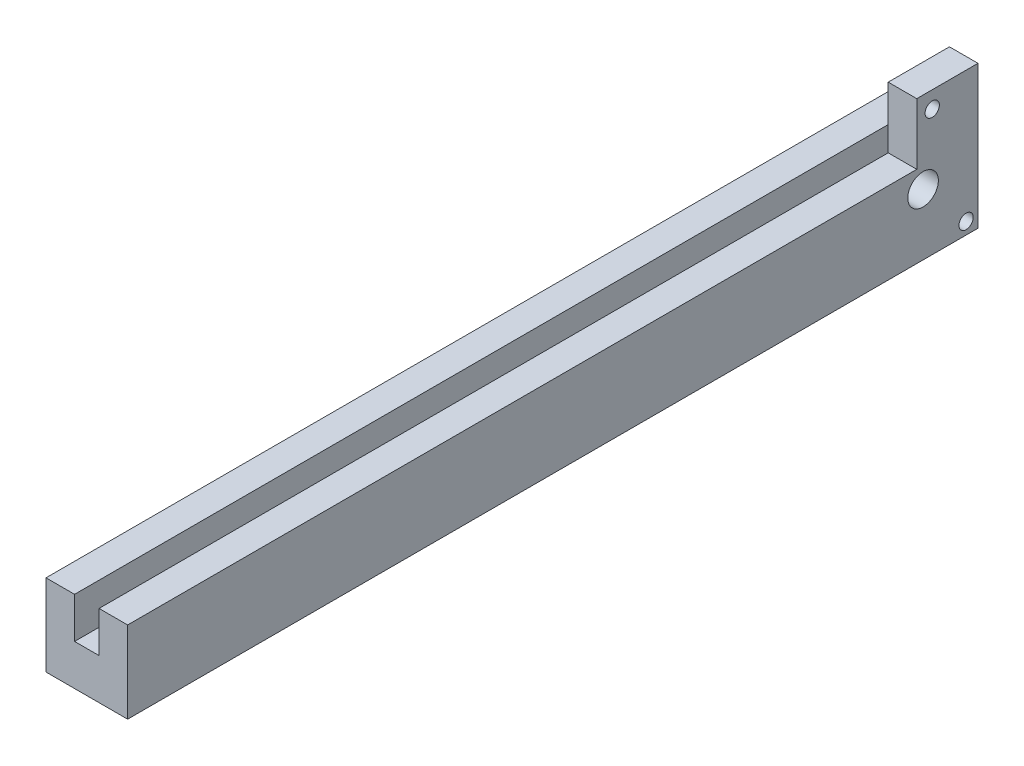
SolidWorks part; units mm, degrees
ref_plane "Front Plane" through (0, 0, 0) normal (0, 0, 1) x (1, 0, 0)
ref_plane "Top Plane" through (0, 0, 0) normal (0, 1, 0) x (1, 0, 0)
ref_plane "Right Plane" through (0, 0, 0) normal (1, 0, 0) x (0, 0, -1)
sketch "Sketch1" plane through (0, 0, 0) normal (0, 0, 1) x (1, 0, 0)
  line L1 (-12, 12) -> (12, 12)
  line L2 (-12, 12) -> (-12, -12)
  line L3 (-12, -12) -> (12, -12)
  line L4 (12, 12) -> (12, -12)
  line L5 (-12, 12) -> (12, -12) construction
  line L6 (-12, -12) -> (12, 12) construction
  point P0 (0, 0)
  dimension "D1" = 24
  dimension "D2" = 24
extrude "Boss-Extrude1" add sketch "Sketch1" along normal blind 250
sketch "Sketch2" plane through (0, 0, 250) normal (0, 0, 1) x (1, 0, 0)
  line L0 (12, 12) -> (-12, 12) construction
  line L1 (0, 0) -> (3.6, 0)
  line L2 (0, 0) -> (0, 12)
  line L3 (0, 12) -> (3.6, 12)
  line L4 (3.6, 0) -> (3.6, 12)
  dimension "D1" = 3.6
extrude "Cut-Extrude1" cut sketch "Sketch2" against normal up to surface (250 mm away) up to face at (0, 0, 0)
mirror "Mirror1" about plane through (0, 0, 0) normal (1, 0, 0) of "Cut-Extrude1"
sketch "Sketch8" plane through (0, 12, 0) normal (0, 1, 0) x (1, 0, 0)
  line L0 (12, -250) -> (12, 0) construction
  line L1 (3.6, 0) -> (12, 0)
  line L2 (3.6, 0) -> (3.6, -18)
  line L3 (3.6, -18) -> (12, -18)
  line L4 (12, 0) -> (12, -18)
  dimension "D1" = 18
extrude "Boss-Extrude2" add sketch "Sketch8" along normal blind 18
sketch "Sketch6" plane through (12, 0, 0) normal (1, 0, 0) x (0, 0, -1)
  line L1 (-250, 12) -> (-18, 12) construction
  line L3 (-250, -12) -> (0, -12) construction
  line L4 (0, -12) -> (0, 30) construction
  circle A0 centre (-3.5, -8.5) radius 2.1
  circle A1 centre (-16.1491, 6) radius 4.5
  circle A2 centre (-13.4597, 25.053) radius 2.1
  dimension "D1" = 4.2
  dimension "D2" = 4.2
  dimension "D7" = 9
  dimension "D3" = 35
  dimension "D5" = 19.2419
  dimension "D6" = 19.2419
  dimension "D4" = 6
  dimension "D8" = 3.5
  dimension "D9" = 3.5
extrude "Cut-Extrude3" cut sketch "Sketch6" against normal up to surface (8.4 mm away) up to face at (3.6, 14, 89.3333)
equation "\"rail width\"= 24"
equation "\"system width\"= 125"
equation "\"system depth\"= 250"
equation "\"internal height\"= 100"
equation "\"carriage height\"= 24"
equation "\"belt width\"= 6"
equation "\"worm gear diameter\"= 8"
equation "\"D1@Sketch1\"=\"rail width\""
equation "\"D2@Sketch1\"=\"rail width\""
equation "\"D1@Boss-Extrude1\"=\"system depth\""
equation "\"D1@Sketch2\"= \"belt width\" * 0.6"
equation "\"motor mounting hole spacing\" = 35"
equation "\"motor hole radius\"= 4.2"
equation "\"motor diameter\"= 28"
equation "\"rotor shelf diameter\"= 9"
equation "\"rotor centre from motor centre\"= 8"
equation "\"pin radius\"= 2.7"
equation "\"pin spacing\"= 9"
equation "\"D1@Sketch6\"=\"motor hole radius\""
equation "\"D2@Sketch6\"=\"motor hole radius\""
equation "\"D5@Sketch6\"=sqr(17.5^2+8^2)"
equation "\"D6@Sketch6\"=sqr(17.5^2+8^2)"
equation "\"D7@Sketch6\"=\"rotor shelf diameter\""
equation "\"D4@Sketch6\"=6"
equation "\"D1@Sketch8\"=18"
equation "\"D1@Boss-Extrude2\"=18"
